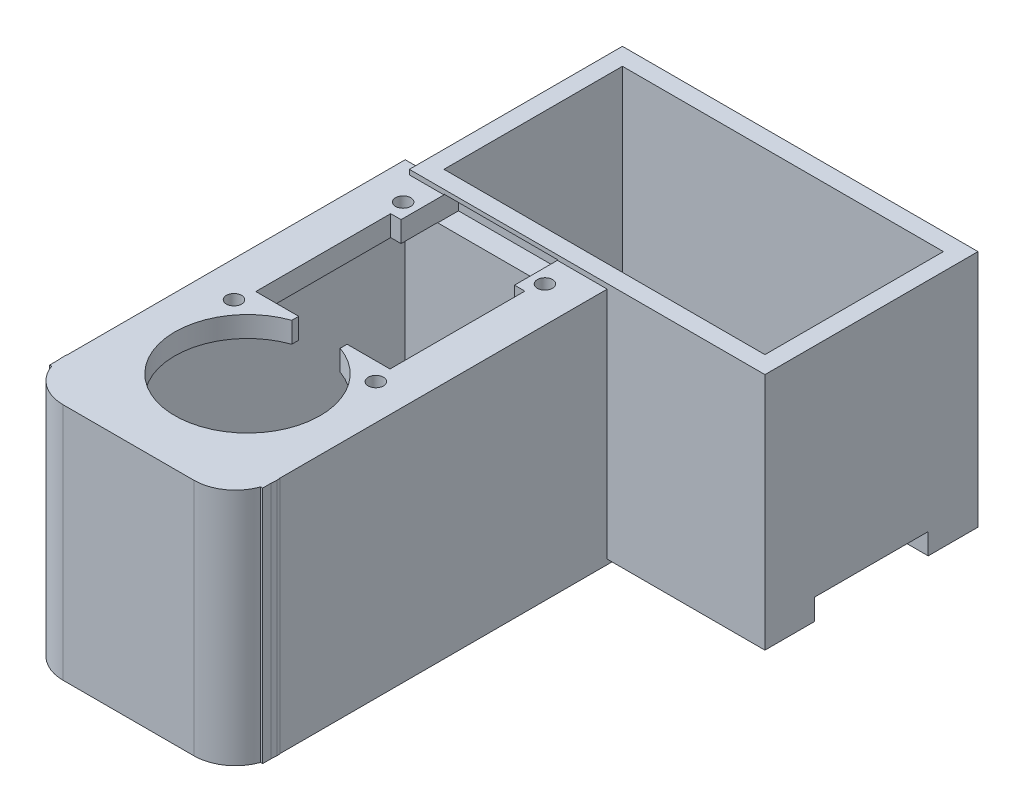
SolidWorks part; units mm, degrees
ref_plane "Front Plane" through (0, 0, 0) normal (0, 0, 1) x (1, 0, 0)
ref_plane "Top Plane" through (0, 0, 0) normal (0, 1, 0) x (1, 0, 0)
ref_plane "Right Plane" through (0, 0, 0) normal (1, 0, 0) x (0, 0, -1)
ref_plane "PZ_m38_200" through (0, 0, -38.2) normal (0, 0, 1) x (1, 0, 0)
sketch "S_box1" plane through (0, 0, -38.2) normal (0, 0, 1) x (1, 0, 0)
  line L0 (-15.4, 2.9) -> (15.4, 2.9)
  line L1 (15.4, 2.9) -> (15.4, 37.4)
  line L2 (15.4, 37.4) -> (-15.4, 37.4)
  line L3 (-15.4, 37.4) -> (-15.4, 2.9)
  dimension "P1" = 15.4
  dimension "P2" = 2.9
  dimension "P3" = 15.4
  dimension "P4" = 2.9
  dimension "P5" = 15.4
  dimension "P6" = 37.4
  dimension "P7" = 15.4
  dimension "P8" = 37.4
extrude "Boss_1" add sketch "S_box1" along normal blind 2.5
ref_plane "PZ_p10_700" through (0, 0, 10.7) normal (0, 0, 1) x (1, 0, 0)
sketch "S_box2" plane through (0, 0, 10.7) normal (0, 0, 1) x (1, 0, 0)
  line L0 (-15.4, 2.9) -> (15.4, 2.9)
  line L1 (15.4, 2.9) -> (15.4, 37.4)
  line L2 (15.4, 37.4) -> (-15.4, 37.4)
  line L3 (-15.4, 37.4) -> (-15.4, 2.9)
  dimension "P1" = 15.4
  dimension "P2" = 2.9
  dimension "P3" = 15.4
  dimension "P4" = 2.9
  dimension "P5" = 15.4
  dimension "P6" = 37.4
  dimension "P7" = 15.4
  dimension "P8" = 37.4
extrude "Boss_2" add sketch "S_box2" along normal blind 2.5
sketch "S_box3" plane through (0, 0, -38.2) normal (0, 0, 1) x (1, 0, 0)
  line L0 (-15.4, 2.9) -> (-12.9, 2.9)
  line L1 (-12.9, 2.9) -> (-12.9, 37.4)
  line L2 (-12.9, 37.4) -> (-15.4, 37.4)
  line L3 (-15.4, 37.4) -> (-15.4, 2.9)
  dimension "P1" = 15.4
  dimension "P2" = 2.9
  dimension "P3" = 12.9
  dimension "P4" = 2.9
  dimension "P5" = 12.9
  dimension "P6" = 37.4
  dimension "P7" = 15.4
  dimension "P8" = 37.4
extrude "Boss_3" add sketch "S_box3" along normal blind 51.4
sketch "S_box4" plane through (0, 0, -38.2) normal (0, 0, 1) x (1, 0, 0)
  line L0 (12.9, 2.9) -> (15.4, 2.9)
  line L1 (15.4, 2.9) -> (15.4, 37.4)
  line L2 (15.4, 37.4) -> (12.9, 37.4)
  line L3 (12.9, 37.4) -> (12.9, 2.9)
  dimension "P1" = 12.9
  dimension "P2" = 2.9
  dimension "P3" = 15.4
  dimension "P4" = 2.9
  dimension "P5" = 15.4
  dimension "P6" = 37.4
  dimension "P7" = 12.9
  dimension "P8" = 37.4
extrude "Boss_4" add sketch "S_box4" along normal blind 51.4
sketch "S_box5" plane through (0, 0, -38.2) normal (0, 0, 1) x (1, 0, 0)
  line L0 (-15.4, 34.4) -> (15.4, 34.4)
  line L1 (15.4, 34.4) -> (15.4, 37.4)
  line L2 (15.4, 37.4) -> (-15.4, 37.4)
  line L3 (-15.4, 37.4) -> (-15.4, 34.4)
  dimension "P1" = 15.4
  dimension "P2" = 34.4
  dimension "P3" = 15.4
  dimension "P4" = 34.4
  dimension "P5" = 15.4
  dimension "P6" = 37.4
  dimension "P7" = 15.4
  dimension "P8" = 37.4
extrude "Boss_5" add sketch "S_box5" along normal blind 51.4
ref_plane "PZ_m67_400" through (0, 0, -67.4) normal (0, 0, 1) x (1, 0, 0)
sketch "S_box6" plane through (0, 0, -67.4) normal (0, 0, 1) x (1, 0, 0)
  line L0 (-13.2, 3.6) -> (-10.7, 3.6)
  line L1 (-10.7, 3.6) -> (-10.7, 38.1)
  line L2 (-10.7, 38.1) -> (-13.2, 38.1)
  line L3 (-13.2, 38.1) -> (-13.2, 3.6)
  dimension "P1" = 13.2
  dimension "P2" = 3.6
  dimension "P3" = 10.7
  dimension "P4" = 3.6
  dimension "P5" = 10.7
  dimension "P6" = 38.1
  dimension "P7" = 13.2
  dimension "P8" = 38.1
extrude "Boss_6" add sketch "S_box6" along normal blind 30.8
sketch "S_box7" plane through (0, 0, -67.4) normal (0, 0, 1) x (1, 0, 0)
  line L0 (35.7, 3.6) -> (38.2, 3.6)
  line L1 (38.2, 3.6) -> (38.2, 38.1)
  line L2 (38.2, 38.1) -> (35.7, 38.1)
  line L3 (35.7, 38.1) -> (35.7, 3.6)
  dimension "P1" = 35.7
  dimension "P2" = 3.6
  dimension "P3" = 38.2
  dimension "P4" = 3.6
  dimension "P5" = 38.2
  dimension "P6" = 38.1
  dimension "P7" = 35.7
  dimension "P8" = 38.1
extrude "Boss_7" add sketch "S_box7" along normal blind 30.8
sketch "S_box8" plane through (0, 0, -67.4) normal (0, 0, 1) x (1, 0, 0)
  line L0 (-13.2, 3.6) -> (38.2, 3.6)
  line L1 (38.2, 3.6) -> (38.2, 38.1)
  line L2 (38.2, 38.1) -> (-13.2, 38.1)
  line L3 (-13.2, 38.1) -> (-13.2, 3.6)
  dimension "P1" = 13.2
  dimension "P2" = 3.6
  dimension "P3" = 38.2
  dimension "P4" = 3.6
  dimension "P5" = 38.2
  dimension "P6" = 38.1
  dimension "P7" = 13.2
  dimension "P8" = 38.1
extrude "Boss_8" add sketch "S_box8" along normal blind 2.5
ref_plane "PZ_m39_100" through (0, 0, -39.1) normal (0, 0, 1) x (1, 0, 0)
sketch "S_box9" plane through (0, 0, -39.1) normal (0, 0, 1) x (1, 0, 0)
  line L0 (-13.2, 3.6) -> (38.2, 3.6)
  line L1 (38.2, 3.6) -> (38.2, 38.1)
  line L2 (38.2, 38.1) -> (-13.2, 38.1)
  line L3 (-13.2, 38.1) -> (-13.2, 3.6)
  dimension "P1" = 13.2
  dimension "P2" = 3.6
  dimension "P3" = 38.2
  dimension "P4" = 3.6
  dimension "P5" = 38.2
  dimension "P6" = 38.1
  dimension "P7" = 13.2
  dimension "P8" = 38.1
extrude "Boss_9" add sketch "S_box9" along normal blind 2.5
sketch "S_box10" plane through (0, 0, -67.4) normal (0, 0, 1) x (1, 0, 0)
  line L0 (-13.2, 3.6) -> (38.2, 3.6)
  line L1 (38.2, 3.6) -> (38.2, 6.6)
  line L2 (38.2, 6.6) -> (-13.2, 6.6)
  line L3 (-13.2, 6.6) -> (-13.2, 3.6)
  dimension "P1" = 13.2
  dimension "P2" = 3.6
  dimension "P3" = 38.2
  dimension "P4" = 3.6
  dimension "P5" = 38.2
  dimension "P6" = 6.6
  dimension "P7" = 13.2
  dimension "P8" = 6.6
extrude "Boss_10" add sketch "S_box10" along normal blind 30.8
ref_plane "PY_p2_900" through (0, 2.9, 0) normal (0, 1, 0) x (1, 0, 0)
sketch "S_prism11" plane through (0, 2.9, 0) normal (0, 1, 0) x (1, 0, 0)
  line L0 (-15.45, -10.75) -> (15.45, -10.75)
  line L1 (15.45, -10.75) -> (15.45, -11.2)
  line L2 (9.45, -17.2) -> (-9.45, -17.2)
  line L3 (-15.45, -11.2) -> (-15.45, -10.75)
  arc A0 (15.45, -11.2) -> (9.45, -17.2) centre (9.4499, -11.1999) cw
  arc A1 (-9.45, -17.2) -> (-15.45, -11.2) centre (-9.4499, -11.1999) cw
extrude "Boss_11" add sketch "S_prism11" along normal blind 34.5
ref_plane "PY_p34_300" through (0, 34.3, 0) normal (0, 1, 0) x (1, 0, 0)
sketch "S_hole12" plane through (0, 34.3, 0) normal (0, 1, 0) x (1, 0, 0)
  circle A0 centre (0, 0) radius 10.5
  dimension "D1_S_hole12" = 21
extrude "Hole_12" cut sketch "S_hole12" along normal blind 3.2
ref_plane "PZ_m30_400" through (0, 0, -30.4) normal (0, 0, 1) x (1, 0, 0)
sketch "S_cut13" plane through (0, 0, -30.4) normal (0, 0, 1) x (1, 0, 0)
  line L0 (-9.7, 34.35) -> (9.7, 34.35)
  line L1 (9.7, 34.35) -> (9.7, 37.5)
  line L2 (9.7, 37.5) -> (-9.7, 37.5)
  line L3 (-9.7, 37.5) -> (-9.7, 34.35)
  dimension "P1" = 9.7
  dimension "P2" = 34.35
  dimension "P3" = 9.7
  dimension "P4" = 34.35
  dimension "P5" = 9.7
  dimension "P6" = 37.5
  dimension "P7" = 9.7
  dimension "P8" = 37.5
extrude "Pocket_13" cut sketch "S_cut13" along normal blind 19.5
ref_plane "PZ_m38_700" through (0, 0, -38.7) normal (0, 0, 1) x (1, 0, 0)
sketch "S_cut14" plane through (0, 0, -38.7) normal (0, 0, 1) x (1, 0, 0)
  line L0 (-8.2, 34.35) -> (8.2, 34.35)
  line L1 (8.2, 34.35) -> (8.2, 37.5)
  line L2 (8.2, 37.5) -> (-8.2, 37.5)
  line L3 (-8.2, 37.5) -> (-8.2, 34.35)
  dimension "P1" = 8.2
  dimension "P2" = 34.35
  dimension "P3" = 8.2
  dimension "P4" = 34.35
  dimension "P5" = 8.2
  dimension "P6" = 37.5
  dimension "P7" = 8.2
  dimension "P8" = 37.5
extrude "Pocket_14" cut sketch "S_cut14" along normal blind 8.3
ref_plane "PZ_m11_000" through (0, 0, -11) normal (0, 0, 1) x (1, 0, 0)
sketch "S_cut15" plane through (0, 0, -11) normal (0, 0, 1) x (1, 0, 0)
  line L0 (-3.5, 34.35) -> (3.5, 34.35)
  line L1 (3.5, 34.35) -> (3.5, 37.5)
  line L2 (3.5, 37.5) -> (-3.5, 37.5)
  line L3 (-3.5, 37.5) -> (-3.5, 34.35)
  dimension "P1" = 3.5
  dimension "P2" = 34.35
  dimension "P3" = 3.5
  dimension "P4" = 34.35
  dimension "P5" = 3.5
  dimension "P6" = 37.5
  dimension "P7" = 3.5
  dimension "P8" = 37.5
extrude "Pocket_15" cut sketch "S_cut15" along normal blind 11
sketch "S_hole16" plane through (0, 34.3, 0) normal (0, 1, 0) x (1, 0, 0)
  circle A0 centre (-10.25, 8.3) radius 1.1
  dimension "D1_S_hole16" = 2.2
  dimension "P2" = 10.25
  dimension "P3" = 8.3
extrude "Hole_16" cut sketch "S_hole16" along normal blind 3.2
sketch "S_hole17" plane through (0, 34.3, 0) normal (0, 1, 0) x (1, 0, 0)
  circle A0 centre (10.25, 8.3) radius 1.1
  dimension "D1_S_hole17" = 2.2
  dimension "P2" = 10.25
  dimension "P3" = 8.3
extrude "Hole_17" cut sketch "S_hole17" along normal blind 3.2
sketch "S_hole18" plane through (0, 34.3, 0) normal (0, 1, 0) x (1, 0, 0)
  circle A0 centre (-10.25, 32.75) radius 1.1
  dimension "D1_S_hole18" = 2.2
  dimension "P2" = 10.25
  dimension "P3" = 32.75
extrude "Hole_18" cut sketch "S_hole18" along normal blind 3.2
sketch "S_hole19" plane through (0, 34.3, 0) normal (0, 1, 0) x (1, 0, 0)
  circle A0 centre (10.25, 32.75) radius 1.1
  dimension "D1_S_hole19" = 2.2
  dimension "P2" = 10.25
  dimension "P3" = 32.75
extrude "Hole_19" cut sketch "S_hole19" along normal blind 3.2
ref_plane "PY_p3_500" through (0, 3.5, 0) normal (0, 1, 0) x (1, 0, 0)
sketch "S_hole20" plane through (0, 3.5, 0) normal (0, 1, 0) x (1, 0, 0)
  circle A0 centre (0, 52) radius 10.5
  dimension "D1_S_hole20" = 21
  dimension "P2" = 52
extrude "Hole_20" cut sketch "S_hole20" along normal blind 3.2
ref_plane "PZ_m61_700" through (0, 0, -61.7) normal (0, 0, 1) x (1, 0, 0)
sketch "S_cut21" plane through (0, 0, -61.7) normal (0, 0, 1) x (1, 0, 0)
  line L0 (10.9, 3.5) -> (30.4, 3.5)
  line L1 (30.4, 3.5) -> (30.4, 6.65)
  line L2 (30.4, 6.65) -> (10.9, 6.65)
  line L3 (10.9, 6.65) -> (10.9, 3.5)
  dimension "P1" = 10.9
  dimension "P2" = 3.5
  dimension "P3" = 30.4
  dimension "P4" = 3.5
  dimension "P5" = 30.4
  dimension "P6" = 6.65
  dimension "P7" = 10.9
  dimension "P8" = 6.65
extrude "Pocket_21" cut sketch "S_cut21" along normal blind 19.4
ref_plane "PZ_m60_200" through (0, 0, -60.2) normal (0, 0, 1) x (1, 0, 0)
sketch "S_cut22" plane through (0, 0, -60.2) normal (0, 0, 1) x (1, 0, 0)
  line L0 (30.4, 3.5) -> (38.7, 3.5)
  line L1 (38.7, 3.5) -> (38.7, 6.65)
  line L2 (38.7, 6.65) -> (30.4, 6.65)
  line L3 (30.4, 6.65) -> (30.4, 3.5)
  dimension "P1" = 30.4
  dimension "P2" = 3.5
  dimension "P3" = 38.7
  dimension "P4" = 3.5
  dimension "P5" = 38.7
  dimension "P6" = 6.65
  dimension "P7" = 30.4
  dimension "P8" = 6.65
extrude "Pocket_22" cut sketch "S_cut22" along normal blind 16.4
ref_plane "PZ_m55_500" through (0, 0, -55.5) normal (0, 0, 1) x (1, 0, 0)
sketch "S_cut23" plane through (0, 0, -55.5) normal (0, 0, 1) x (1, 0, 0)
  line L0 (0, 3.5) -> (11, 3.5)
  line L1 (11, 3.5) -> (11, 6.65)
  line L2 (11, 6.65) -> (0, 6.65)
  line L3 (0, 6.65) -> (0, 3.5)
  dimension "P1" = 3.5
  dimension "P2" = 11
  dimension "P3" = 3.5
  dimension "P4" = 11
  dimension "P5" = 6.65
  dimension "P6" = 6.65
extrude "Pocket_23" cut sketch "S_cut23" along normal blind 7
sketch "S_hole24" plane through (0, 3.5, 0) normal (0, 1, 0) x (1, 0, 0)
  circle A0 centre (8.3, 62.25) radius 1.1
  dimension "D1_S_hole24" = 2.2
  dimension "P2" = 8.3
  dimension "P3" = 62.25
extrude "Hole_24" cut sketch "S_hole24" along normal blind 3.2
sketch "S_hole25" plane through (0, 3.5, 0) normal (0, 1, 0) x (1, 0, 0)
  circle A0 centre (8.3, 41.75) radius 1.1
  dimension "D1_S_hole25" = 2.2
  dimension "P2" = 8.3
  dimension "P3" = 41.75
extrude "Hole_25" cut sketch "S_hole25" along normal blind 3.2
sketch "S_hole26" plane through (0, 3.5, 0) normal (0, 1, 0) x (1, 0, 0)
  circle A0 centre (32.75, 62.25) radius 1.1
  dimension "D1_S_hole26" = 2.2
  dimension "P2" = 32.75
  dimension "P3" = 62.25
extrude "Hole_26" cut sketch "S_hole26" along normal blind 3.2
sketch "S_hole27" plane through (0, 3.5, 0) normal (0, 1, 0) x (1, 0, 0)
  circle A0 centre (32.75, 41.75) radius 1.1
  dimension "D1_S_hole27" = 2.2
  dimension "P2" = 32.75
  dimension "P3" = 41.75
extrude "Hole_27" cut sketch "S_hole27" along normal blind 3.2
equation "\"plate_t\" = 3"
equation "\"clearance\" = 0.5"
